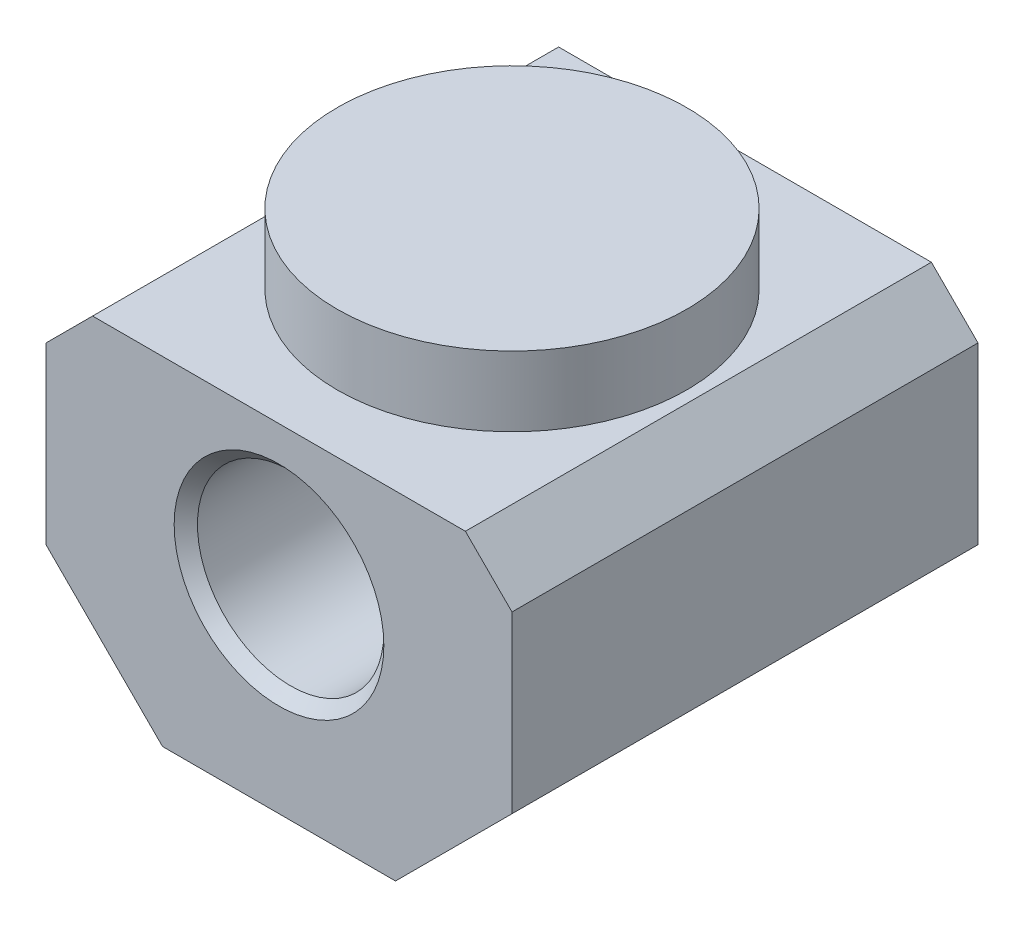
SolidWorks part; units mm, degrees
ref_plane "Front" through (0, 0, 0) normal (0, 0, 1) x (1, 0, 0)
ref_plane "Top" through (0, 0, 0) normal (0, 1, 0) x (1, 0, 0)
ref_plane "Right" through (0, 0, 0) normal (1, 0, 0) x (0, 0, -1)
ref_plane "Plane1" through (0, 6, 0) normal (0, 1, 0) x (1, 0, 0)
sketch "Sketch1" plane through (0, 0, 0) normal (0, 1, 0) x (1, 0, 0)
  line L0 (10, 10) -> (-10, 10)
  line L1 (-10, 10) -> (-10, -10)
  line L2 (-10, -10) -> (10, -10)
  line L3 (10, -10) -> (10, 10)
  point P4 (10, 0)
  point P6 (0, 10)
  dimension "D1" = 20
extrude "Boss-Extrude1" add sketch "Sketch1" against normal blind 14.5
sketch "Sketch2" plane through (0, 0, 0) normal (0, 1, 0) x (-1, 0, 0)
  circle A0 centre (0, 0) radius 7.5
  dimension "D1" = 15
extrude "Boss-Extrude2" add sketch "Sketch2" along normal blind 3
hole_wizard "Ø8.0 (8) Diameter Hole1" positions "Sketch4" profile "Sketch3" hole size "Ø8.0" standard "ANSI Metric"
sketch "Sketch4" plane through (0, 0, 10) normal (0, 0, 1) x (1, 0, 0)
  line L0 (-10, 0) -> (10, 0) construction
  line L1 (0, 0) -> (0, -6) construction
  point P0 (0, -6)
  dimension "D1" = 6
sketch "Sketch3" plane through (0, -6, 10) normal (1, 0, 0) x (0, -1, 0)
  line L0 (0, 0) -> (0, 20)
  line L1 (0, 20) -> (4, 20)
  line L2 (4, 20) -> (4, 0)
  line L5 (4, 0) -> (0, 0)
  line L11 (0, -6.35) -> (0, 107.95) construction
  dimension "Thru Hole Dia." = 8
  dimension "Thru Hole Depth" = 20
chamfer "Chamfer1" distance 5 angle 45 2 edges at (10, -14.5, 0) (-10, -14.5, 0)
chamfer "Chamfer2" distance 2 angle 45 2 edges at (-10, 0, 0) (10, 0, 0)
chamfer "Chamfer3" distance 0.5 angle 45 2 edges at (4, -6, 10) (4, -6, -10)
